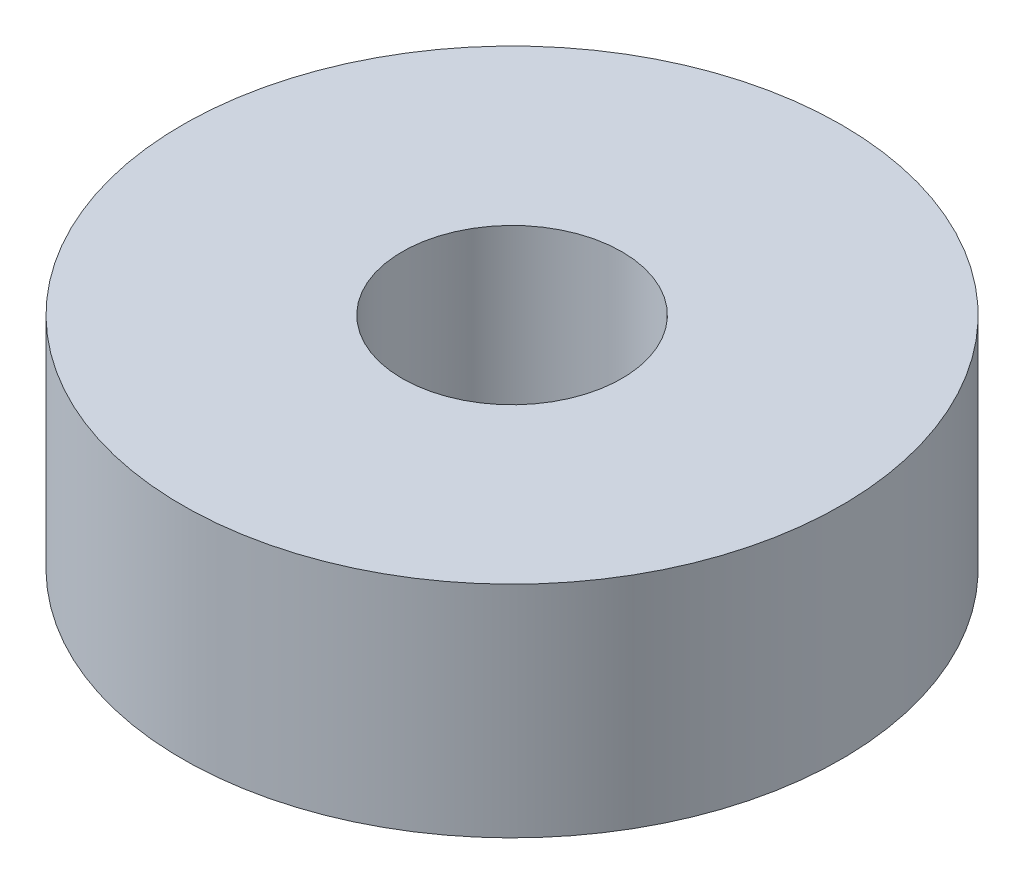
SolidWorks part; units mm, degrees
ref_plane "前视基准面" through (0, 0, 0) normal (0, 0, 1) x (1, 0, 0)
ref_plane "上视基准面" through (0, 0, 0) normal (0, 1, 0) x (1, 0, 0)
ref_plane "右视基准面" through (0, 0, 0) normal (1, 0, 0) x (0, 0, -1)
other "Configuration Table"
sketch "草图1" plane through (0, 0, 0) normal (0, 0, 1) x (1, 0, 0)
  line L0 (0, 0) -> (0, 20) construction
  line L2 (5, 0) -> (15, 0)
  line L3 (5, 0) -> (5, 10)
  line L4 (5, 10) -> (15, 10)
  line L5 (15, 0) -> (15, 10)
revolve "旋转1" add sketch "草图1" angle 360 about L0
